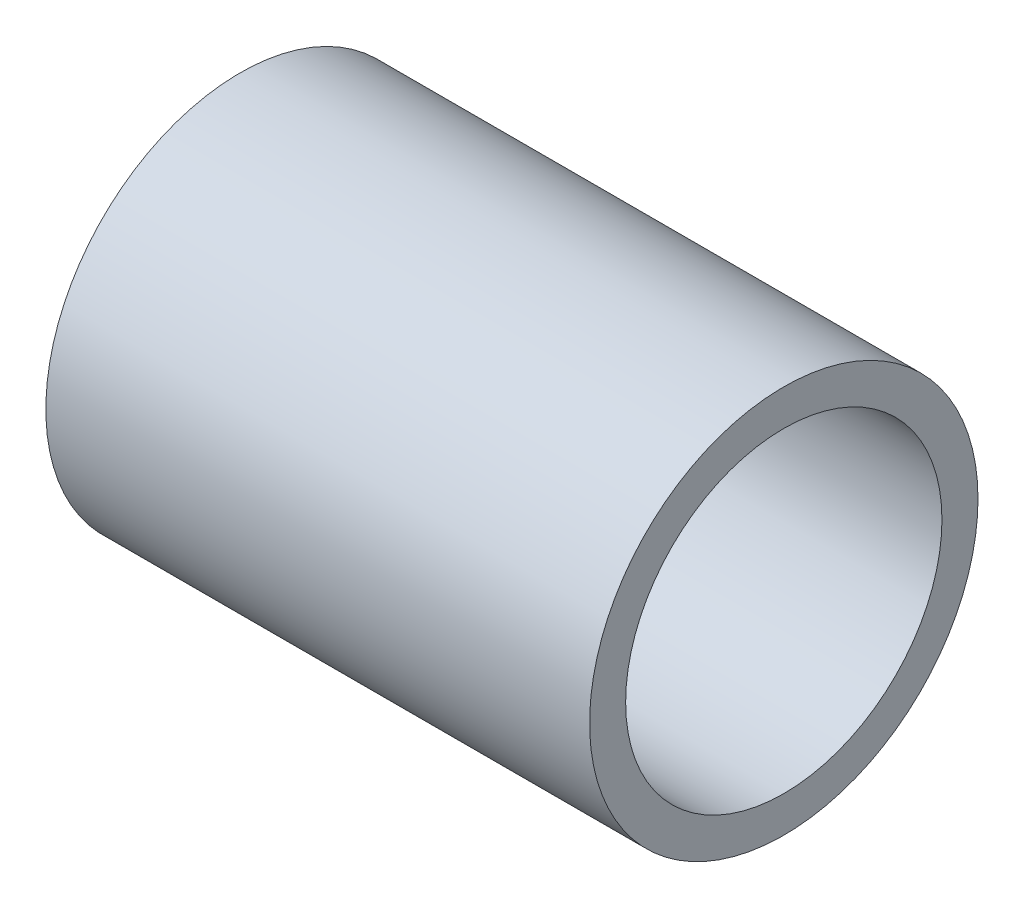
SolidWorks part; units mm, degrees
ref_plane "Front Plane" through (0, 0, 0) normal (0, 0, 1) x (1, 0, 0)
ref_plane "Top Plane" through (0, 0, 0) normal (0, 1, 0) x (1, 0, 0)
ref_plane "Right Plane" through (0, 0, 0) normal (1, 0, 0) x (0, 0, -1)
sketch "Sketch1" plane through (0, 0, 0) normal (1, 0, 0) x (0, 0, -1)
  circle A0 centre (0, 0) radius 6.4643
  circle A1 centre (0, 0) radius 7.9375
  dimension "D1" = 12.9286
  dimension "D2" = 15.875
extrude "Boss-Extrude1" add sketch "Sketch1" along normal blind 22.225
